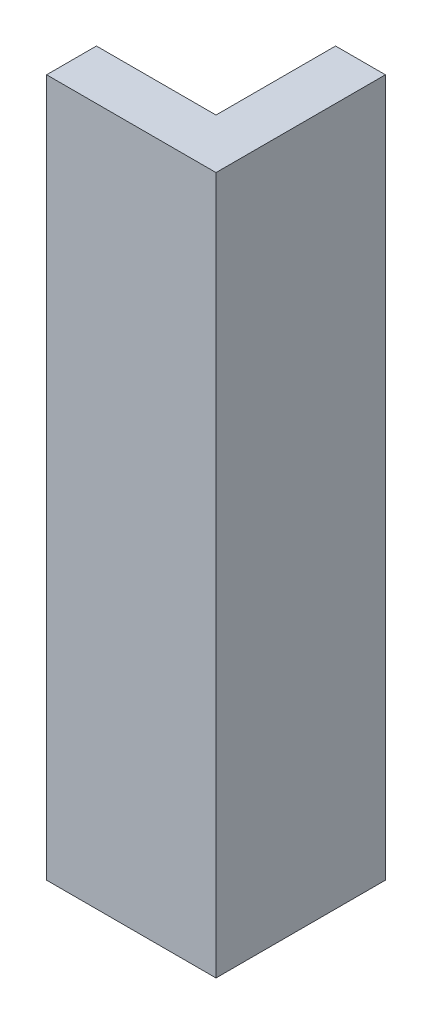
SolidWorks part; units mm, degrees
ref_plane "前视基准面" through (0, 0, 0) normal (0, 0, 1) x (1, 0, 0)
ref_plane "上视基准面" through (0, 0, 0) normal (0, 1, 0) x (1, 0, 0)
ref_plane "右视基准面" through (0, 0, 0) normal (1, 0, 0) x (0, 0, -1)
sketch "草图1" plane through (0, 0, 0) normal (0, 1, 0) x (1, 0, 0)
  line L1 (0, 0) -> (17, 0)
  line L2 (0, 0) -> (0, -17)
  line L3 (0, -17) -> (17, -17)
  line L4 (17, 0) -> (17, -17)
  dimension "D1" = 17
  dimension "D2" = 17
extrude "凸台-拉伸1" add sketch "草图1" along normal blind 70
sketch "草图2" plane through (0, 70, 0) normal (0, 1, 0) x (1, 0, 0)
  line L0 (17, -17) -> (17, 0) construction
  line L1 (0, 0) -> (12, 0)
  line L2 (0, 0) -> (0, -12)
  line L3 (0, -12) -> (12, -12)
  line L4 (12, 0) -> (12, -12)
  line L5 (0, -17) -> (17, -17) construction
  dimension "D1" = 5
  dimension "D2" = 5
extrude "切除-拉伸1" cut sketch "草图2" against normal blind 66
sketch "草图3" plane through (0, 0, 0) normal (0, -1, 0) x (-1, 0, 0)
  line L0 (-9.5745, -2.4255) -> (-2.4255, -2.4255) construction
  line L1 (-2.4255, -2.4255) -> (-2.4255, -9.5745) construction
  line L2 (-2.4255, -9.5745) -> (-9.5745, -9.5745) construction
  line L3 (-9.5745, -9.5745) -> (-9.5745, -2.4255) construction
  line L4 (-9.5745, -2.4255) -> (-9.5745, 0) construction
  line L5 (-17, 0) -> (0, 0) construction
  line L6 (-9.5745, -2.4255) -> (-12, -2.4255) construction
  line L7 (-12, -12) -> (-12, 0) construction
  line L8 (0, -9.5745) -> (-2.4255, -9.5745) construction
  line L9 (0, 0) -> (0, -17) construction
  line L10 (-2.4255, -9.5745) -> (-2.4255, -12) construction
  line L11 (0, -12) -> (-12, -12) construction
  circle A0 centre (-9.5745, -2.4255) radius 1.5
  circle A1 centre (-2.4255, -2.4255) radius 1.5
  circle A2 centre (-9.5745, -9.5745) radius 1.5
  circle A3 centre (-2.4255, -9.5745) radius 1.5
  dimension "D1" = 3
extrude "切除-拉伸2" cut sketch "草图3" against normal blind 8
